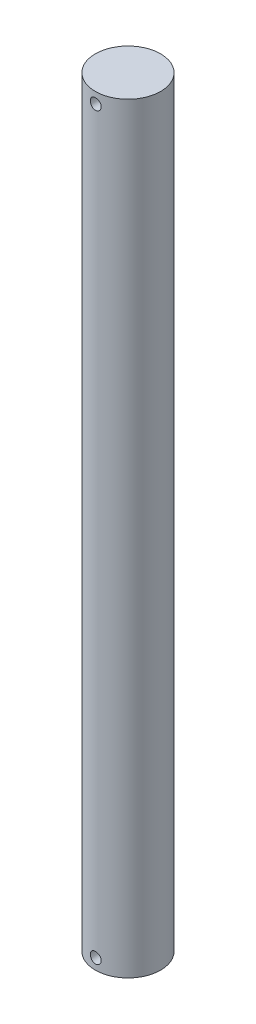
SolidWorks part; units mm, degrees
ref_plane "Front Plane" through (0, 0, 0) normal (0, 0, 1) x (1, 0, 0)
ref_plane "Top Plane" through (0, 0, 0) normal (0, 1, 0) x (1, 0, 0)
ref_plane "Right Plane" through (0, 0, 0) normal (1, 0, 0) x (0, 0, -1)
sketch "Sketch1" plane through (0, 0, 0) normal (0, 1, 0) x (1, 0, 0)
  circle A0 centre (0, 0) radius 30
  dimension "D1" = 60
extrude "Boss-Extrude1" add sketch "Sketch1" along normal blind 700
sketch "Sketch2" plane through (0, 0, 0) normal (0, 0, 1) x (1, 0, 0)
  line L1 (30, 700) -> (-30, 700) construction
  circle A0 centre (0, 690) radius 5
  circle A1 centre (0, 10) radius 5
  dimension "D1" = 10
  dimension "D2" = 10
  dimension "D3" = 10
  dimension "D4" = 10
extrude "Cut-Extrude1" cut sketch "Sketch2" against normal through all both and the other way through all
